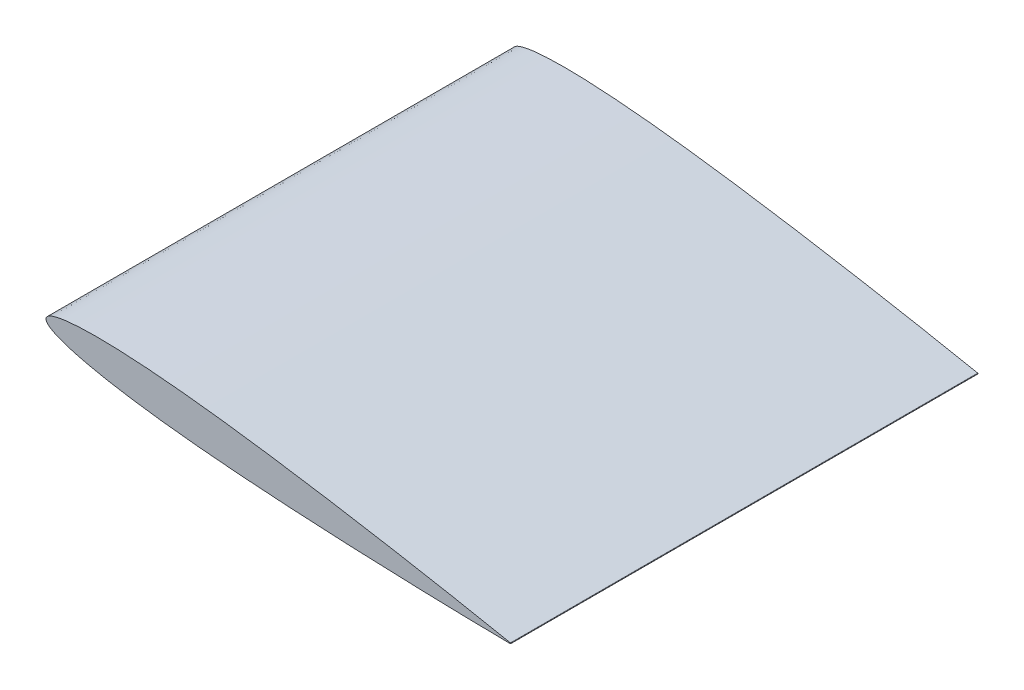
SolidWorks part; units mm, degrees
ref_plane "Front Plane" through (0, 0, 0) normal (0, 0, 1) x (1, 0, 0)
ref_plane "Top Plane" through (0, 0, 0) normal (0, 1, 0) x (1, 0, 0)
ref_plane "Right Plane" through (0, 0, 0) normal (1, 0, 0) x (0, 0, -1)
curve "Curve1"
  spline degree 3 poles (25.4, 0.0213, 0) (25.3979, 0.0215, 0) (25.3896, 0.0223, 0) (25.3708, 0.0241, 0) (25.3395, 0.027, 0) (25.2957, 0.0311, 0) (25.2395, 0.0363, 0) (25.1709, 0.0426, 0) (25.0901, 0.0501, 0) (24.997, 0.0587, 0) (24.8917, 0.0683, 0) (24.7744, 0.079, 0) (24.6452, 0.0907, 0) (24.5043, 0.1034, 0) (24.3517, 0.117, 0) (24.1875, 0.1315, 0) (24.0121, 0.147, 0) (23.8254, 0.1632, 0) (23.6278, 0.1803, 0) (23.4194, 0.1981, 0) (23.2005, 0.2167, 0) (22.9711, 0.2359, 0) (22.7317, 0.2558, 0) (22.4823, 0.2763, 0) (22.2233, 0.2973, 0) (21.9549, 0.3188, 0) (21.6773, 0.3408, 0) (21.3909, 0.3631, 0) (21.0959, 0.3859, 0) (20.7926, 0.4089, 0) (20.4814, 0.4323, 0) (20.1624, 0.4558, 0) (19.8361, 0.4795, 0) (19.5028, 0.5034, 0) (19.1627, 0.5274, 0) (18.8163, 0.5513, 0) (18.4638, 0.5753, 0) (18.1056, 0.5992, 0) (17.7421, 0.6229, 0) (17.3737, 0.6466, 0) (17.0006, 0.6699, 0) (16.6232, 0.693, 0) (16.242, 0.7158, 0) (15.8573, 0.7382, 0) (15.4695, 0.7601, 0) (15.079, 0.7816, 0) (14.6861, 0.8025, 0) (14.2912, 0.8228, 0) (13.8948, 0.8424, 0) (13.4972, 0.8613, 0) (13.0988, 0.8794, 0) (12.7, 0.8966, 0) (12.3012, 0.9129, 0) (11.9028, 0.9283, 0) (11.5052, 0.9426, 0) (11.1088, 0.9558, 0) (10.7139, 0.9679, 0) (10.3211, 0.9787, 0) (9.9305, 0.9884, 0) (9.5427, 0.9966, 0) (9.158, 1.0035, 0) (8.7768, 1.009, 0) (8.3995, 1.0131, 0) (8.0264, 1.0156, 0) (7.6579, 1.0165, 0) (7.2944, 1.016, 0) (6.9362, 1.0137, 0) (6.5837, 1.0099, 0) (6.2373, 1.0044, 0) (5.8972, 0.9972, 0) (5.5639, 0.9883, 0) (5.2375, 0.9777, 0) (4.9186, 0.9655, 0) (4.6073, 0.9514, 0) (4.304, 0.9358, 0) (4.009, 0.9184, 0) (3.7226, 0.8995, 0) (3.4451, 0.8788, 0) (3.1766, 0.8566, 0) (2.9176, 0.8328, 0) (2.6682, 0.8075, 0) (2.4287, 0.7806, 0) (2.1994, 0.7523, 0) (1.9804, 0.7226, 0) (1.7719, 0.6915, 0) (1.5743, 0.6591, 0) (1.3876, 0.6255, 0) (1.2121, 0.5906, 0) (1.0479, 0.5546, 0) (0.8952, 0.5175, 0) (0.7542, 0.4794, 0) (0.6249, 0.4403, 0) (0.5074, 0.4002, 0) (0.402, 0.3593, 0) (0.3086, 0.3175, 0) (0.2274, 0.275, 0) (0.1583, 0.2316, 0) (0.1014, 0.1873, 0) (0.0567, 0.1422, 0) (0.0243, 0.096, 0) (0.0045, 0.0485, 0) (-0.0022, 0, 0) (0.0045, -0.0485, 0) (0.0243, -0.096, 0) (0.0567, -0.1422, 0) (0.1014, -0.1873, 0) (0.1583, -0.2316, 0) (0.2274, -0.275, 0) (0.3086, -0.3175, 0) (0.402, -0.3593, 0) (0.5074, -0.4002, 0) (0.6249, -0.4403, 0) (0.7542, -0.4794, 0) (0.8952, -0.5175, 0) (1.0479, -0.5546, 0) (1.2121, -0.5906, 0) (1.3876, -0.6255, 0) (1.5743, -0.6591, 0) (1.7719, -0.6915, 0) (1.9804, -0.7226, 0) (2.1994, -0.7523, 0) (2.4287, -0.7806, 0) (2.6682, -0.8075, 0) (2.9176, -0.8328, 0) (3.1766, -0.8566, 0) (3.4451, -0.8788, 0) (3.7226, -0.8995, 0) (4.009, -0.9184, 0) (4.304, -0.9358, 0) (4.6073, -0.9514, 0) (4.9186, -0.9655, 0) (5.2375, -0.9777, 0) (5.5639, -0.9883, 0) (5.8972, -0.9972, 0) (6.2373, -1.0044, 0) (6.5837, -1.0099, 0) (6.9362, -1.0137, 0) (7.2944, -1.016, 0) (7.6579, -1.0165, 0) (8.0264, -1.0156, 0) (8.3995, -1.0131, 0) (8.7768, -1.009, 0) (9.158, -1.0035, 0) (9.5427, -0.9966, 0) (9.9305, -0.9884, 0) (10.3211, -0.9787, 0) (10.7139, -0.9679, 0) (11.1088, -0.9558, 0) (11.5052, -0.9426, 0) (11.9028, -0.9283, 0) (12.3012, -0.9129, 0) (12.7, -0.8966, 0) (13.0988, -0.8794, 0) (13.4972, -0.8613, 0) (13.8948, -0.8424, 0) (14.2912, -0.8228, 0) (14.6861, -0.8025, 0) (15.079, -0.7816, 0) (15.4695, -0.7601, 0) (15.8573, -0.7382, 0) (16.242, -0.7158, 0) (16.6232, -0.693, 0) (17.0006, -0.6699, 0) (17.3737, -0.6466, 0) (17.7421, -0.6229, 0) (18.1056, -0.5992, 0) (18.4638, -0.5753, 0) (18.8163, -0.5513, 0) (19.1627, -0.5274, 0) (19.5028, -0.5034, 0) (19.8361, -0.4795, 0) (20.1624, -0.4558, 0) (20.4814, -0.4323, 0) (20.7926, -0.4089, 0) (21.0959, -0.3859, 0) (21.3909, -0.3631, 0) (21.6773, -0.3408, 0) (21.9549, -0.3188, 0) (22.2233, -0.2973, 0) (22.4823, -0.2763, 0) (22.7317, -0.2558, 0) (22.9711, -0.2359, 0) (23.2005, -0.2167, 0) (23.4194, -0.1981, 0) (23.6278, -0.1803, 0) (23.8254, -0.1632, 0) (24.0121, -0.147, 0) (24.1875, -0.1315, 0) (24.3517, -0.117, 0) (24.5043, -0.1034, 0) (24.6452, -0.0907, 0) (24.7744, -0.079, 0) (24.8917, -0.0683, 0) (24.997, -0.0587, 0) (25.0901, -0.0501, 0) (25.1709, -0.0426, 0) (25.2395, -0.0363, 0) (25.2957, -0.0311, 0) (25.3395, -0.027, 0) (25.3708, -0.0241, 0) (25.3896, -0.0223, 0) (25.3979, -0.0215, 0) (25.4, -0.0213, 0) knots 0 0 0 0 0.000123 0.000491 0.001103 0.00196 0.003061 0.004403 0.005987 0.00781 0.00987 0.012166 0.014695 0.017455 0.020443 0.023655 0.027089 0.030742 0.034609 0.038686 0.042971 0.047458 0.052143 0.057021 0.062088 0.067338 0.072766 0.078367 0.084136 0.090066 0.096151 0.102387 0.108765 0.115282 0.121928 0.128698 0.135587 0.142585 0.149687 0.156886 0.164174 0.171545 0.17899 0.186504 0.194077 0.201703 0.209374 0.217082 0.224821 0.232582 0.240357 0.248139 0.255921 0.263694 0.271451 0.279184 0.286886 0.29455 0.302166 0.309729 0.317231 0.324663 0.332021 0.339295 0.346479 0.353566 0.360549 0.367422 0.374177 0.380809 0.387311 0.393676 0.399899 0.405973 0.411894 0.417656 0.423252 0.428678 0.43393 0.439001 0.443888 0.448586 0.453092 0.4574 0.461508 0.465412 0.46911 0.472598 0.475875 0.478937 0.481785 0.484418 0.486835 0.489038 0.491029 0.492814 0.494398 0.495793 0.497018 0.498099 0.499075 0.5 0.500925 0.501901 0.502982 0.504207 0.505602 0.507186 0.508971 0.510962 0.513165 0.515582 0.518215 0.521063 0.524125 0.527402 0.53089 0.534588 0.538492 0.5426 0.546908 0.551414 0.556112 0.560999 0.56607 0.571322 0.576748 0.582344 0.588106 0.594027 0.600101 0.606324 0.612689 0.619191 0.625823 0.632578 0.639451 0.646434 0.653521 0.660705 0.667979 0.675337 0.682769 0.690271 0.697834 0.70545 0.713114 0.720816 0.728549 0.736306 0.744079 0.751861 0.759643 0.767418 0.775179 0.782918 0.790626 0.798297 0.805923 0.813496 0.82101 0.828455 0.835826 0.843114 0.850313 0.857415 0.864413 0.871302 0.878072 0.884718 0.891235 0.897613 0.903849 0.909934 0.915864 0.921633 0.927234 0.932662 0.937912 0.942979 0.947857 0.952542 0.957029 0.961314 0.965391 0.969258 0.972911 0.976345 0.979557 0.982545 0.985305 0.987834 0.99013 0.99219 0.994013 0.995597 0.996939 0.99804 0.998897 0.999509 0.999877 1 1 1 1
sketch "Sketch1" plane through (0, 0, 0) normal (0, 0, 1) x (1, 0, 0)
  line L0 (-47.3641, 4.9782) -> (142.0923, -14.9345) construction
  line L1 (-47.3641, 4.9782) -> (-45.8456, 19.4254) construction
  line L2 (141.2719, -20.9147) -> (-49.2281, -20.9147) construction
  arc A0 (141.9642, -14.7602) -> (141.9306, -15.0782) centre (141.9326, -14.9176) cw
  spline S1 degree 3 poles (141.9642, -14.7602) (141.7178, -14.7107) (141.3332, -14.6334) (140.7799, -14.5223) (140.2738, -14.4211) (139.677, -14.3018) (138.9898, -14.1648) (138.213, -14.0099) (137.3473, -13.8382) (136.3936, -13.6495) (135.353, -13.4438) (134.2262, -13.2224) (133.0144, -12.9847) (131.7189, -12.7316) (130.3407, -12.4633) (128.8814, -12.1808) (127.3424, -11.8836) (125.725, -11.5729) (124.0309, -11.2493) (122.2619, -10.9126) (120.4195, -10.5638) (118.5055, -10.2035) (116.5219, -9.8316) (114.4706, -9.4496) (112.3536, -9.0575) (110.173, -8.6557) (107.9308, -8.2452) (105.6294, -7.8263) (103.2709, -7.3996) (100.8575, -6.9661) (98.3919, -6.5258) (95.8763, -6.0797) (93.3131, -5.6285) (90.7051, -5.1723) (88.0544, -4.7126) (85.364, -4.2494) (82.6364, -3.7833) (79.8741, -3.3156) (77.0801, -2.8464) (74.2569, -2.3766) (71.4075, -1.9068) (67.564, -1.2799) (63.6943, -0.658) (59.8018, -0.0441) (56.8627, 0.4144) (53.9142, 0.8679) (50.9592, 1.3162) (48.0008, 1.7588) (45.0415, 2.1941) (42.0844, 2.622) (39.1323, 3.0418) (36.1881, 3.4522) (33.2547, 3.853) (30.335, 4.243) (27.4319, 4.6222) (24.5479, 4.9888) (21.6863, 5.3434) (18.8495, 5.6839) (16.0405, 6.0114) (13.2618, 6.3235) (9.6265, 6.7172) (6.0399, 7.0825) (2.5054, 7.4165) (-0.0809, 7.6481) (-2.6211, 7.8621) (-5.1126, 8.0585) (-7.553, 8.2362) (-9.9397, 8.396) (-12.2706, 8.5366) (-14.5433, 8.6586) (-16.7555, 8.7615) (-18.9051, 8.8455) (-21.6398, 8.9302) (-24.2845, 8.9795) (-26.8362, 8.9896) (-28.6421, 8.9777) (-30.3738, 8.9476) (-32.0293, 8.8983) (-33.6071, 8.8308) (-35.1056, 8.7451) (-36.5233, 8.6412) (-37.8588, 8.5197) (-39.1108, 8.3805) (-40.278, 8.2243) (-41.3595, 8.0514) (-42.354, 7.8614) (-43.2607, 7.6553) (-44.0788, 7.4335) (-44.8076, 7.1953) (-45.4467, 6.942) (-45.9957, 6.6729) (-46.4545, 6.3882) (-46.8233, 6.0872) (-47.1011, 5.768) (-47.2862, 5.4295) (-47.3737, 5.0734) (-47.3626, 4.7069) (-47.2522, 4.3372) (-47.0472, 3.967) (-46.7494, 3.5957) (-46.3601, 3.2214) (-45.8795, 2.8435) (-45.3074, 2.4623) (-44.6445, 2.0771) (-43.8907, 1.6893) (-43.047, 1.2984) (-42.1141, 0.9049) (-41.0927, 0.5099) (-39.9838, 0.1134) (-38.7886, -0.2843) (-37.5079, -0.6821) (-36.1431, -1.0797) (-34.6956, -1.4766) (-33.1667, -1.8721) (-31.558, -2.2662) (-29.8708, -2.6573) (-28.1072, -3.0462) (-25.6097, -3.5693) (-23.013, -4.0735) (-20.321, -4.5618) (-18.2012, -4.9287) (-16.0163, -5.2901) (-13.7682, -5.6455) (-11.4594, -5.9949) (-9.0919, -6.3372) (-6.6682, -6.6731) (-4.1907, -7.0014) (-1.6619, -7.3227) (0.9158, -7.6364) (4.4421, -8.048) (8.0259, -8.44) (11.6632, -8.8142) (14.4458, -9.0894) (17.2613, -9.3559) (20.1066, -9.6154) (22.9792, -9.8664) (25.8761, -10.1102) (28.7944, -10.3458) (31.7312, -10.5743) (34.6836, -10.795) (37.6485, -11.0087) (40.6232, -11.2147) (43.6045, -11.4139) (46.5894, -11.6063) (49.575, -11.7915) (52.5585, -11.9703) (55.5367, -12.1427) (58.5067, -12.3082) (62.4415, -12.5208) (66.3558, -12.7209) (70.2455, -12.9106) (73.1302, -13.0464) (75.9892, -13.1767) (78.8196, -13.3013) (81.6186, -13.421) (84.3834, -13.5349) (87.1113, -13.6438) (89.7995, -13.7479) (92.4453, -13.8466) (95.0462, -13.9407) (97.5995, -14.0298) (100.1027, -14.1142) (102.5534, -14.1944) (104.9489, -14.2698) (107.2871, -14.3408) (109.5656, -14.4077) (111.782, -14.4703) (113.9342, -14.529) (116.0201, -14.5838) (118.0376, -14.6345) (119.9847, -14.6819) (121.8592, -14.7257) (123.6596, -14.7659) (125.3839, -14.8032) (127.0305, -14.8372) (128.5976, -14.8681) (130.0838, -14.8966) (131.4875, -14.9221) (132.8074, -14.9452) (134.0421, -14.9658) (135.1903, -14.9847) (136.2509, -15.0008) (137.223, -15.0155) (138.1055, -15.0284) (138.8974, -15.0392) (139.5981, -15.0488) (140.2067, -15.0568) (140.9111, -15.0659) (141.4755, -15.0726) (141.8677, -15.0774) (141.9306, -15.0782) knots 0 0 0 0 0.00196 0.003061 0.004403 0.005987 0.00781 0.00987 0.012166 0.014695 0.017455 0.020443 0.023655 0.027089 0.030742 0.034609 0.038686 0.042971 0.047458 0.052143 0.057021 0.062088 0.067338 0.072766 0.078367 0.084136 0.090066 0.096151 0.102387 0.108765 0.115282 0.121928 0.128698 0.135587 0.142585 0.149687 0.156886 0.164174 0.171545 0.17899 0.186504 0.194077 0.209374 0.217082 0.224821 0.232582 0.240357 0.248139 0.255921 0.263694 0.271451 0.279184 0.286886 0.29455 0.302166 0.309729 0.317231 0.324663 0.332021 0.339295 0.346479 0.360549 0.367422 0.374177 0.380809 0.387311 0.393676 0.399899 0.405973 0.411894 0.417656 0.423252 0.428678 0.439001 0.443888 0.448586 0.453092 0.4574 0.461508 0.465412 0.46911 0.472598 0.475875 0.478937 0.481785 0.484418 0.486835 0.489038 0.491029 0.492814 0.494398 0.495793 0.497018 0.498099 0.499075 0.5 0.500925 0.501901 0.502982 0.504207 0.505602 0.507186 0.508971 0.510962 0.513165 0.515582 0.518215 0.521063 0.524125 0.527402 0.53089 0.534588 0.538492 0.5426 0.546908 0.551414 0.556112 0.560999 0.571322 0.576748 0.582344 0.588106 0.594027 0.600101 0.606324 0.612689 0.619191 0.625823 0.632578 0.639451 0.653521 0.660705 0.667979 0.675337 0.682769 0.690271 0.697834 0.70545 0.713114 0.720816 0.728549 0.736306 0.744079 0.751861 0.759643 0.767418 0.775179 0.782918 0.790626 0.805923 0.813496 0.82101 0.828455 0.835826 0.843114 0.850313 0.857415 0.864413 0.871302 0.878072 0.884718 0.891235 0.897613 0.903849 0.909934 0.915864 0.921633 0.927234 0.932662 0.937912 0.942979 0.947857 0.952542 0.957029 0.961314 0.965391 0.969258 0.972911 0.976345 0.979557 0.982545 0.985305 0.987834 0.99013 0.99219 0.994013 0.995597 0.996939 0.999509 1 1 1 1
  point P7 (0, 0)
  point P8 (0, 0)
  dimension "D1" = 190.5
  dimension "D2" = 47.625
  dimension "D3" = 6
extrude "Boss-Extrude1" add sketch "Sketch1" against normal blind 190.5
